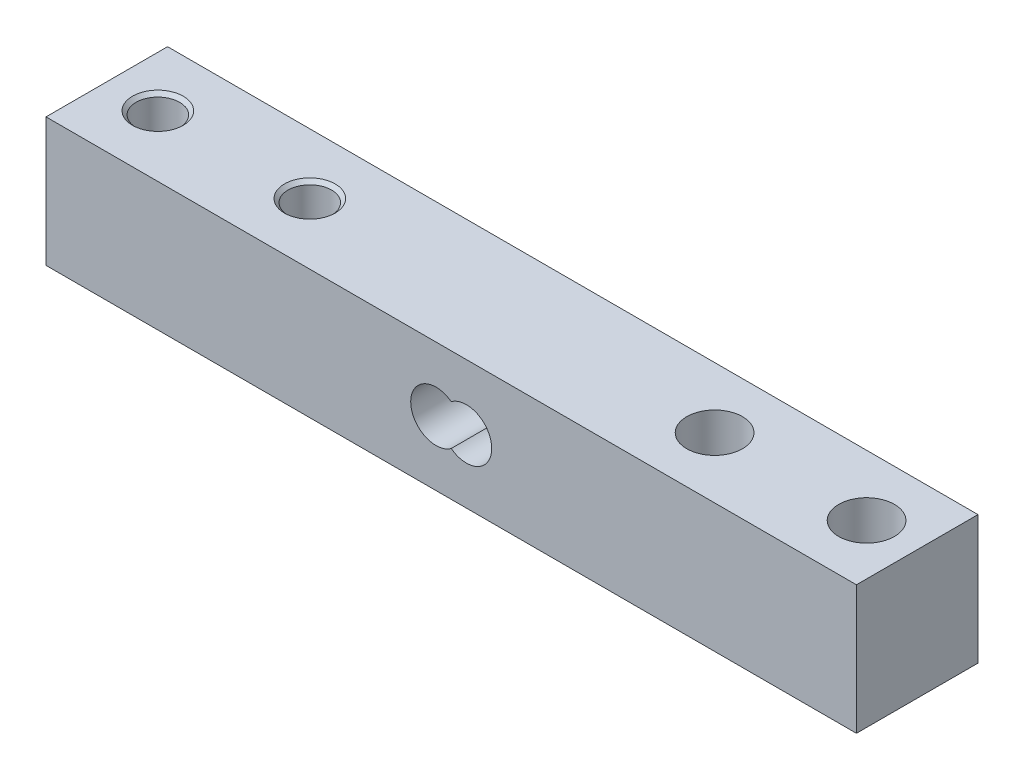
SolidWorks part; units mm, degrees
ref_plane "Front Plane" through (0, 0, 0) normal (0, 0, 1) x (1, 0, 0)
ref_plane "Top Plane" through (0, 0, 0) normal (0, 1, 0) x (1, 0, 0)
ref_plane "Right Plane" through (0, 0, 0) normal (1, 0, 0) x (0, 0, -1)
sketch "Sketch1" plane through (0, 0, 0) normal (0, 0, 1) x (1, 0, 0)
  line L0 (0, 0) -> (-80, 0)
  line L1 (-80, 12.7) -> (0, 12.7)
  line L2 (0, 12.7) -> (0, 0)
  line L3 (-80, 0) -> (-80, 12.7)
  line L4 (-80, 6.35) -> (0, 6.35) construction
  line L5 (-40, 12.7) -> (-40, 0) construction
  circle A0 centre (-41.5, 6.35) radius 2.5
  circle A1 centre (-38.5, 6.35) radius 2.5
  dimension "D3" = 5
  dimension "D1" = 80
  dimension "D2" = 12.7
  dimension "D4" = 1.5
  dimension "D5" = 1.5
extrude "Base Shape" add sketch "Sketch1" along normal blind 12 contours L3 L0 L2 L1 A1 A0
sketch "Sketch2" plane through (0, 0, 0) normal (0, 1, 0) x (1, 0, 0)
  line L0 (-80, -6) -> (0, -6) construction
  line L1 (-80, -12) -> (-80, 0) construction
  line L2 (0, -12) -> (0, 0) construction
  line L3 (-40, 0) -> (-40, -12) construction
  line L4 (-80, 0) -> (0, 0) construction
  line L5 (-75, -4.7275) -> (-75, -7.1904) construction
  line L6 (-60, -4.7275) -> (-60, -7.1904) construction
  line L7 (-80, -6) -> (0, -6) construction
  dimension "D1" = 5
  dimension "D2" = 15
hole_wizard "CSK for M4 Flat Head Machine Screw1" positions "Sketch3" profile "Sketch4" countersink size "M4" standard "ANSI Metric" end condition through all
sketch "Sketch3" plane through (0, 12.7, 0) normal (0, 1, 0) x (1, 0, 0)
  line L0 (-75, -4.7275) -> (-75, -7.1904) construction
  line L1 (-60, -4.7275) -> (-60, -7.1904) construction
  point P0 (-75, -5.959)
  point P4 (-60, -5.959)
sketch "Sketch4" plane through (-75, 12.7, 5.959) normal (1, 0, 0) x (0, 0, 1)
  line L0 (0, 0) -> (0, 12.7)
  line L1 (0, 12.7) -> (2.15, 12.7)
  line L2 (2.15, 12.7) -> (2.15, 0.35)
  line L3 (2.15, 0.35) -> (2.5, 0)
  line L5 (2.5, 0) -> (0, 0)
  line L6 (-2.15, 0.35) -> (-2.5, 0) construction
  line L11 (0, -6.35) -> (0, 107.95) construction
  dimension "Thru Hole Dia." = 4.3
  dimension "Thru Hole Depth" = 12.7
  dimension "Near C'Sink Dia." = 5
  dimension "Near C'Sink Angle" = 90
sketch "Sketch5" plane through (0, 0, 0) normal (0, -1, 0) x (-1, 0, 0)
  line L0 (20, -7.9292) -> (20, -2.7573) construction
  line L2 (5, -7.9292) -> (5, -2.7573) construction
  line L3 (80, -6) -> (0, -6) construction
  line L4 (0, -12) -> (0, 0) construction
  dimension "D1" = 15
  dimension "D2" = 5
hole_wizard "CSK for M5 Countersunk Flat Head1" positions "Sketch14" profile "Sketch15" countersink size "M5" standard "BSI" end condition through all
sketch "Sketch14" plane through (0, 0, 0) normal (0, -1, 0) x (-1, 0, 0)
  line L0 (80, -6) -> (0, -6) construction
  line L1 (20, -7.9292) -> (20, -2.7573) construction
  line L2 (5, -7.9292) -> (5, -2.7573) construction
  point P0 (20, -6)
  point P6 (5, -6)
sketch "Sketch15" plane through (-20, 0, 6) normal (1, 0, 0) x (0, 0, -1)
  line L0 (0, 0) -> (0, 12.7)
  line L1 (0, 12.7) -> (2.75, 12.7)
  line L2 (2.75, 12.7) -> (2.75, 0.25)
  line L3 (2.75, 0.25) -> (3, 0)
  line L5 (3, 0) -> (0, 0)
  line L6 (-2.75, 0.25) -> (-3, 0) construction
  line L11 (0, -6.35) -> (0, 107.95) construction
  dimension "Thru Hole Dia." = 5.5
  dimension "Thru Hole Depth" = 12.7
  dimension "Near C'Sink Dia." = 6
  dimension "Near C'Sink Angle" = 90
